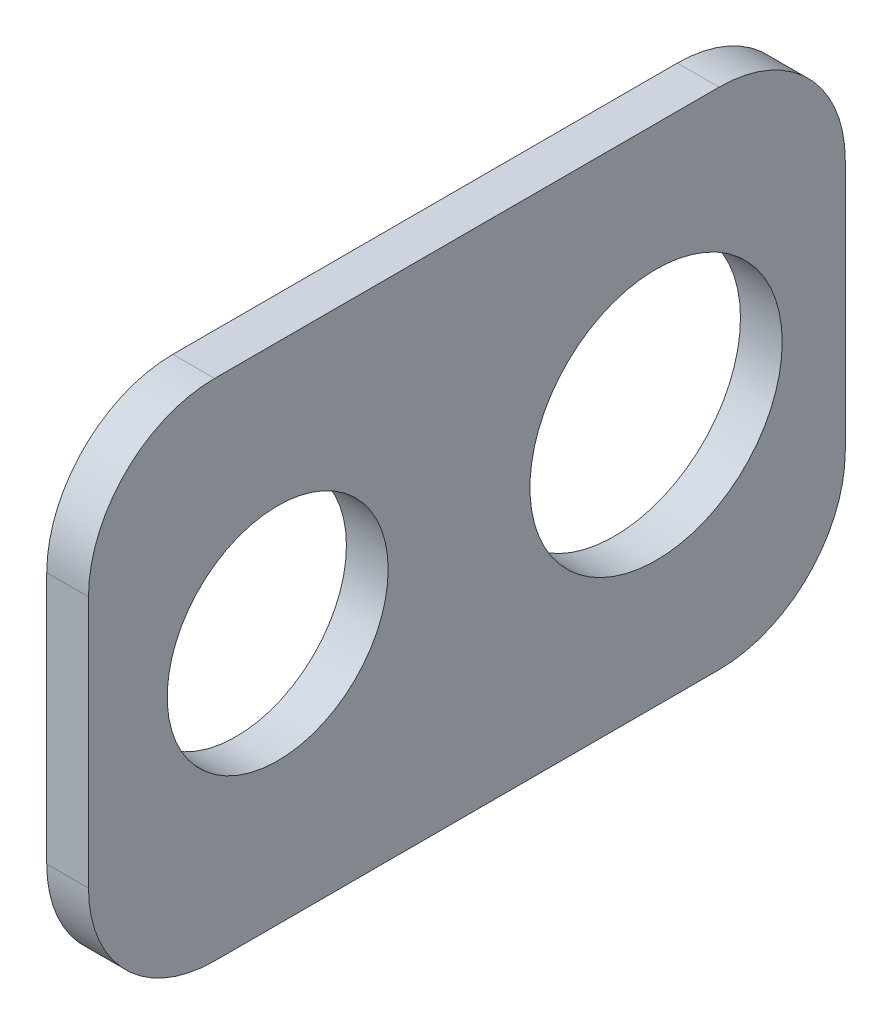
SolidWorks part; units mm, degrees
material "ASTM A36 Steel"
ref_plane "Front Plane" through (0, 0, 0) normal (1, 0, 0) x (0, 1, 0)
ref_plane "Top Plane" through (0, 0, 0) normal (0, 0, 1) x (0, 1, 0)
ref_plane "Right Plane" through (0, 0, 0) normal (0, 1, 0) x (-1, 0, 0)
sketch "Sketch1" plane through (0, 0, 0) normal (1, 0, 0) x (0, 1, 0)
  line L1 (0, 0) -> (50.8, 0)
  line L2 (0, 0) -> (0, 76.2)
  line L3 (0, 76.2) -> (50.8, 76.2)
  line L4 (50.8, 0) -> (50.8, 76.2)
  dimension "D1" = 76.2
  dimension "D2" = 50.8
extrude "Boss-Extrude1" add sketch "Sketch1" along normal blind 4.203 contours L4 L3 L2 L1
sketch "Sketch3" plane through (4.203, 0, 0) normal (1, 0, 0) x (0, 1, 0)
  line L0 (0, 76.2) -> (50.8, 76.2) construction
  line L1 (0, 0) -> (50.8, 0) construction
  circle A0 centre (25.4, 57.15) radius 11.1252
  circle A1 centre (25.4, 19.05) radius 12.7
  dimension "D1" = 22.2504
  dimension "D2" = 25.4
  dimension "D3" = 19.05
  dimension "D4" = 19.05
extrude "Cut-Extrude1" cut sketch "Sketch3" against normal through all
fillet "Fillet2" radius 12.7 4 edges at (2.1015, 0, 0) (2.1015, 50.8, 0) (2.1015, 50.8, 76.2) (2.1015, 0, 76.2)
equation "\"LOAD\"= 600'Force applied to link (lbf)"
equation "\"LENGTH\"= 3'Length/Height of Link (in)"
equation "\"WIDTH\"= 2'Width of Link (in)"
equation "\"SAFETY_FAC\"= 4'Given safety factor "
equation "\"STRENGTH\"= 36259.4'Yield Strength of A36 Steel (psi)"
equation "\"DIAMETER_A\"= 0.876'Calculated Diameter of Feature A (in)"
equation "\"DIAMETER_1\"= 1'Given Diameter of Link Hole (in)"
equation "\"DIFFERENCE\"= \"WIDTH\" - \"DIAMETER_1\"'Calculated Largest Differnce of Width (in)"
equation "\"LINK_THICK\" = ( \"LOAD\" * \"SAFETY_FAC\" ) / ( \"DIFFERENCE\" * \"STRENGTH\" ) * 2.5'Calculated Thickness of the link (in)"
equation "\"D1@Sketch1\"=\"LENGTH\""
equation "\"D2@Sketch1\"=\"WIDTH\""
equation "\"D1@Boss-Extrude1\"=\"LINK_THICK\""
equation "\"D1@Sketch3\"=\"DIAMETER_A\""
equation "\"D2@Sketch3\"=\"DIAMETER_1\""
equation "\"D3@Sketch3\"=\"LENGTH\"/4"
equation "\"D4@Sketch3\"=\"LENGTH\"/4"
